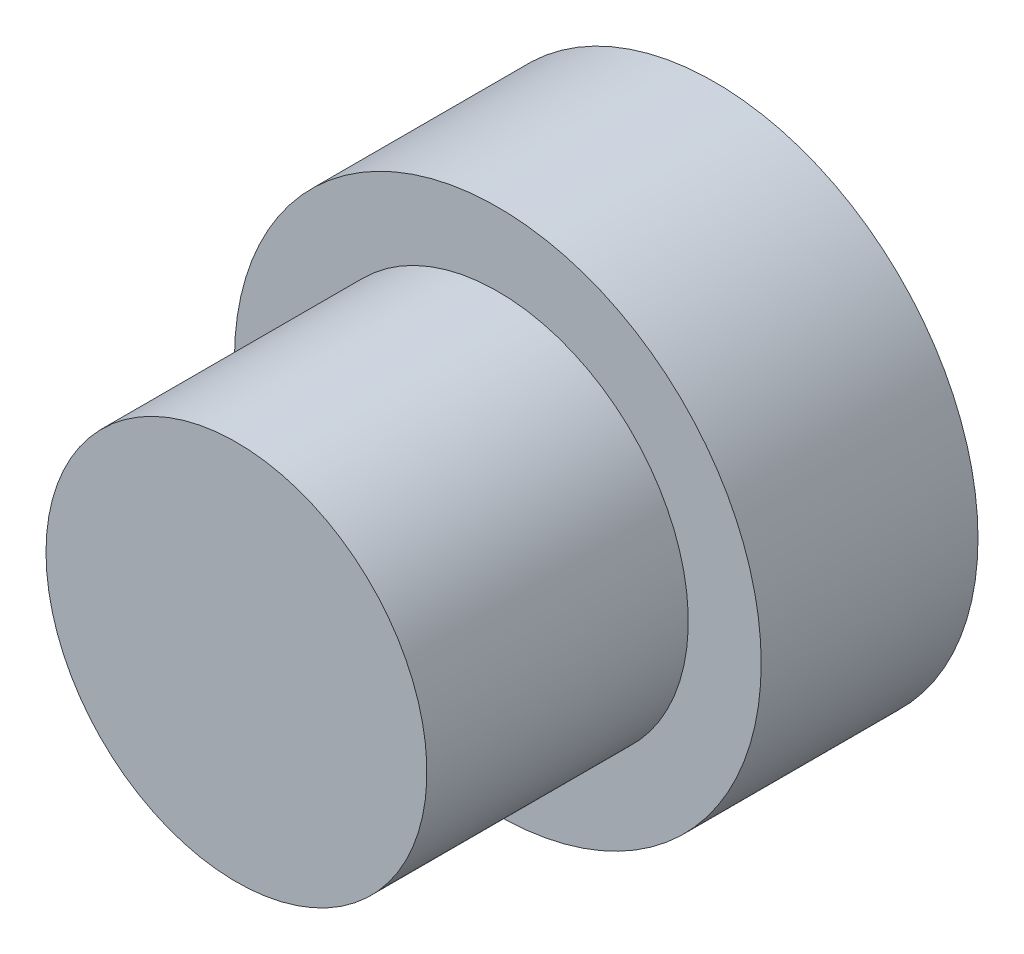
SolidWorks part; units mm, degrees
ref_plane "Front Plane" through (0, 0, 0) normal (0, 0, 1) x (1, 0, 0)
ref_plane "Top Plane" through (0, 0, 0) normal (0, 1, 0) x (1, 0, 0)
ref_plane "Right Plane" through (0, 0, 0) normal (1, 0, 0) x (0, 0, -1)
sketch "Sketch2" plane through (0, 0, 0) normal (0, 0, 1) x (1, 0, 0)
  circle A1 centre (12.9571, -1.0547) radius 13
extrude "Boss-Extrude1" add sketch "Sketch2" along normal blind 10.7
sketch "Sketch3" plane through (0, 0, 10.7) normal (0, 0, 1) x (1, 0, 0)
  circle A1 centre (12.9571, -1.0547) radius 9.4
extrude "Boss-Extrude2" add sketch "Sketch3" along normal blind 12.9 contours A1
